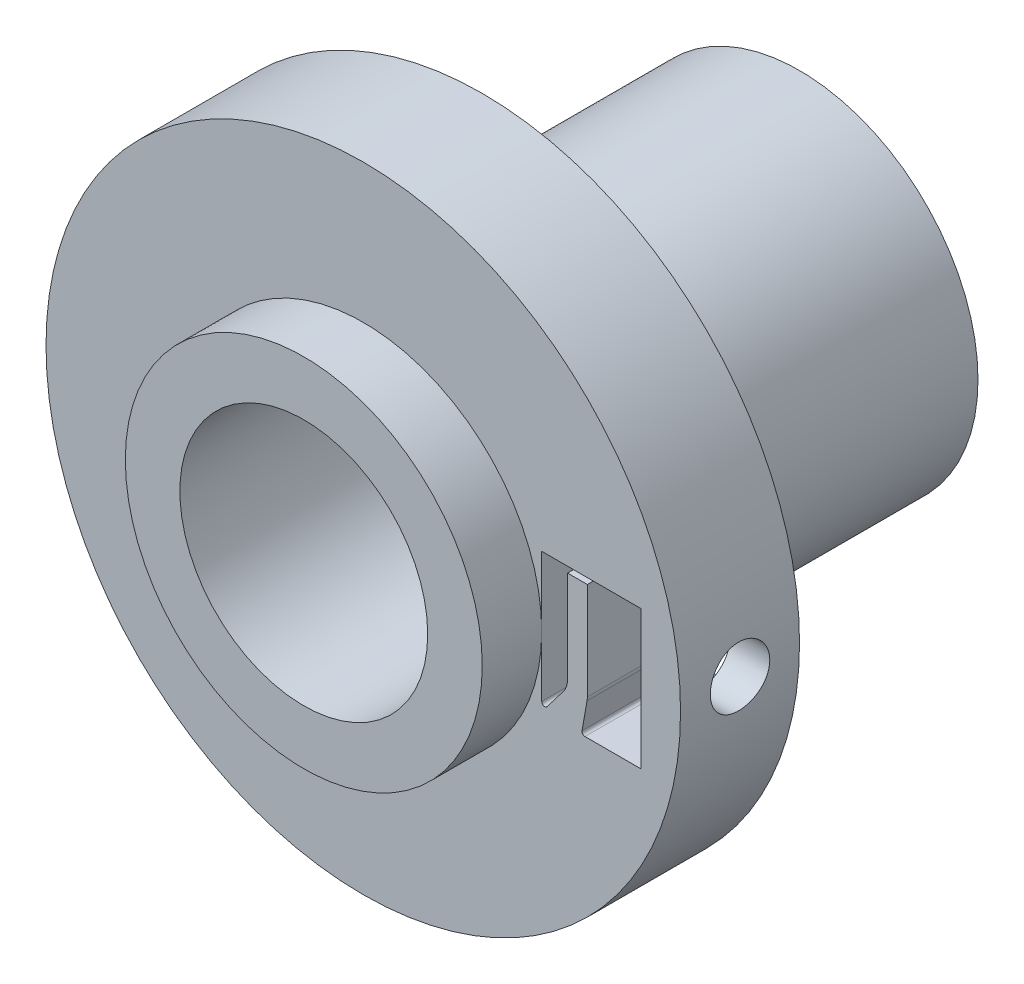
SolidWorks part; units mm, degrees
ref_plane "Ebene vorne" through (0, 0, 0) normal (0, 0, 1) x (1, 0, 0)
ref_plane "Ebene oben" through (0, 0, 0) normal (0, 1, 0) x (1, 0, 0)
ref_plane "Ebene rechts" through (0, 0, 0) normal (1, 0, 0) x (0, 0, -1)
sketch "Skizze1" plane through (0, 0, 0) normal (0, 0, 1) x (1, 0, 0)
  circle A0 centre (0, 0) radius 9
  circle A1 centre (0, 0) radius 6.25
  dimension "D1" = 18
  dimension "D2" = 12.5
extrude "Aufsatz-Linear austragen1" add sketch "Skizze1" along normal mid plane 16
sketch "Skizze2" plane through (0, 0, 8) normal (0, 0, 1) x (1, 0, 0)
  circle A0 centre (0, 0) radius 6.25
  circle A1 centre (0, 0) radius 16
  dimension "D1" = 32
extrude "Aufsatz-Linear austragen2" add sketch "Skizze2" along normal blind 6
sketch "Skizze3" plane through (0, 0, 8) normal (0, 0, -1) x (-1, 0, 0)
  line L0 (55, 0) -> (-55, 0) construction
  line L1 (-9, -3.5) -> (-10.0944, -2.0689)
  line L2 (-14, 3.5) -> (-9, 3.5)
  line L3 (-14, 3.5) -> (-14, -3.5)
  line L4 (-14, -3.5) -> (-11, -3.5)
  line L5 (-9, 3.5) -> (-9, -3.5)
  line L6 (-14, 3.5) -> (-9, -3.5) construction
  line L7 (-14, -3.5) -> (-9, 3.5) construction
  line L8 (-10.3, -1.4615) -> (-10.3, 3.2)
  line L9 (-10.3, 3.2) -> (-11.3, 3.2)
  line L10 (-11.3, 3.2) -> (-11.3, -1.7124)
  line L11 (-11.2848, -1.8862) -> (-11, -3.5)
  arc A1 (-10.0944, -2.0689) -> (-10.3, -1.4615) centre (-9.3, -1.4615) cw
  arc A2 (-11.3, -1.7124) -> (-11.2848, -1.8862) centre (-10.3, -1.7124) ccw
  point P0 (-11, 0)
  point P37 (-10.3, -1.8)
  point P43 (-11.3, -1.8)
  dimension "D1" = 9
  dimension "D5" = 1
  dimension "D11" = 1
  dimension "D2" = 7
  dimension "D3" = 5
  dimension "D4" = 3.5
  dimension "D6" = 1
  dimension "D7" = 0.3
  dimension "D8" = 1.3
  dimension "D9" = 14
  dimension "D10" = 5
  dimension "D12" = 2
extrude "Schnitt-Linear austragen1" cut sketch "Skizze3" against normal blind 6
sketch "Skizze4" plane through (0, 0, 0) normal (1, 0, 0) x (0, 0, -1)
  line L0 (55, 0) -> (-55, 0) construction
  line L1 (-14, 16) -> (-14, -16) construction
  circle A0 centre (-11, 0) radius 1.5
  dimension "D1" = 3
  dimension "D2" = 3
extrude "Schnitt-Linear austragen2" cut sketch "Skizze4" against normal blind 4 from offset 17
sketch "Skizze5" plane through (0, 0, 14) normal (0, 0, 1) x (1, 0, 0)
  circle A0 centre (0, 0) radius 6.25
  circle A1 centre (0, 0) radius 9
  dimension "D1" = 12.5
  dimension "D2" = 18
extrude "Aufsatz-Linear austragen3" add sketch "Skizze5" along normal blind 3
fillet "Verrundung1" radius 0.15 1 edges at (9, -3.5, 11)
fillet "Verrundung2" radius 0.15 1 edges at (11, -3.5, 11)
